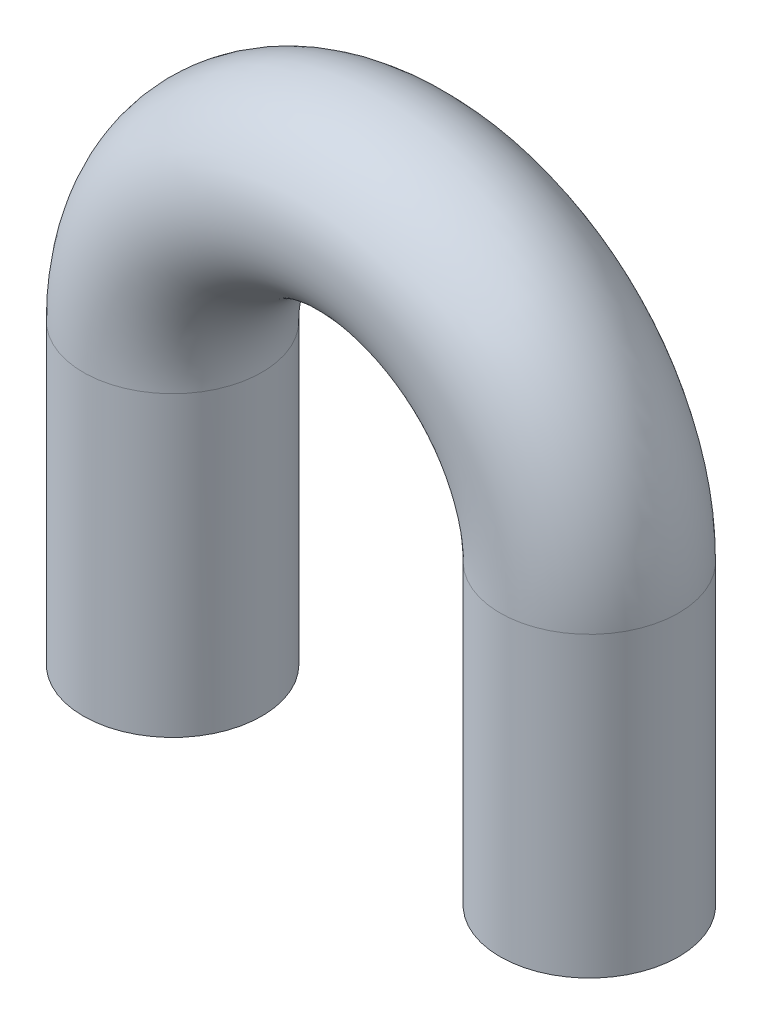
SolidWorks part; units mm, degrees
ref_plane "Front Plane" through (0, 0, 0) normal (0, 0, 1) x (1, 0, 0)
ref_plane "Top Plane" through (0, 0, 0) normal (0, 1, 0) x (1, 0, 0)
ref_plane "Right Plane" through (0, 0, 0) normal (1, 0, 0) x (0, 0, -1)
sketch "Sketch1" plane through (0, 0, 0) normal (0, 1, 0) x (1, 0, 0)
  line L0 (-8.89, 0) -> (8.89, 0) construction
  circle A0 centre (-8.89, 0) radius 3.81
  circle A1 centre (8.89, 0) radius 3.81
  point P4 (0, 0)
  dimension "D1" = 7.62
  dimension "D2" = 17.78
extrude "Boss-Extrude1" add sketch "Sketch1" along normal blind 12.7
sketch "Sketch2" plane through (0, 0, 0) normal (0, 0, 1) x (1, 0, 0)
  line L0 (-5.08, 12.7) -> (-12.7, 12.7) construction
  line L1 (-12.7, 12.7) -> (-5.08, 12.7) construction
  arc A0 (-8.89, 12.7) -> (8.89, 12.7) centre (0, 12.7) cw
  point P5 (-8.89, 12.7)
ref_plane "Plane1" through (0, 12.7, 0) normal (0, 1, 0) x (1, 0, 0)
sketch "Sketch3" plane through (0, 12.7, 0) normal (0, 1, 0) x (1, 0, 0)
  line L0 (0, 9.3183) -> (0, -9.8198) construction
  line L1 (-12.7, 0) -> (-5.08, 0) construction
  circle A0 centre (-8.89, 0) radius 3.81
revolve "Revolve1" add sketch "Sketch3" angle 180 about L0
